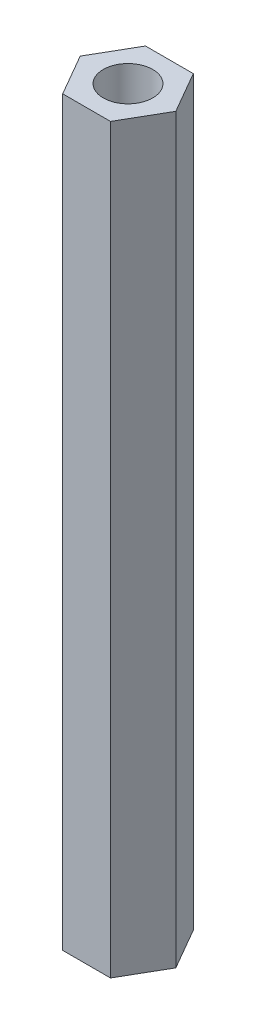
SolidWorks part; units mm, degrees
ref_plane "Alzado" through (0, 0, 0) normal (0, 0, 1) x (1, 0, 0)
ref_plane "Planta" through (0, 0, 0) normal (0, 1, 0) x (1, 0, 0)
ref_plane "Vista lateral" through (0, 0, 0) normal (1, 0, 0) x (0, 0, -1)
sketch "Croquis1" plane through (0, 0, 0) normal (0, 1, 0) x (1, 0, 0)
  line L1 (2.9, 0) -> (1.45, 2.5115)
  line L2 (1.45, 2.5115) -> (-1.45, 2.5115)
  line L3 (-1.45, 2.5115) -> (-2.9, 0)
  line L4 (-2.9, 0) -> (-1.45, -2.5115)
  line L5 (-1.45, -2.5115) -> (1.45, -2.5115)
  line L6 (1.45, -2.5115) -> (2.9, 0)
  circle A0 centre (0, 0) radius 2.9 construction
extrude "Saliente-Extruir2" add sketch "Croquis1" along normal blind 45
sketch "Croquis2" plane through (0, 45, 0) normal (0, 1, 0) x (1, 0, 0)
  circle A0 centre (0, 0) radius 1.5
  dimension "D1" = 3
extrude "Cortar-Extruir1" cut sketch "Croquis2" against normal blind 45
